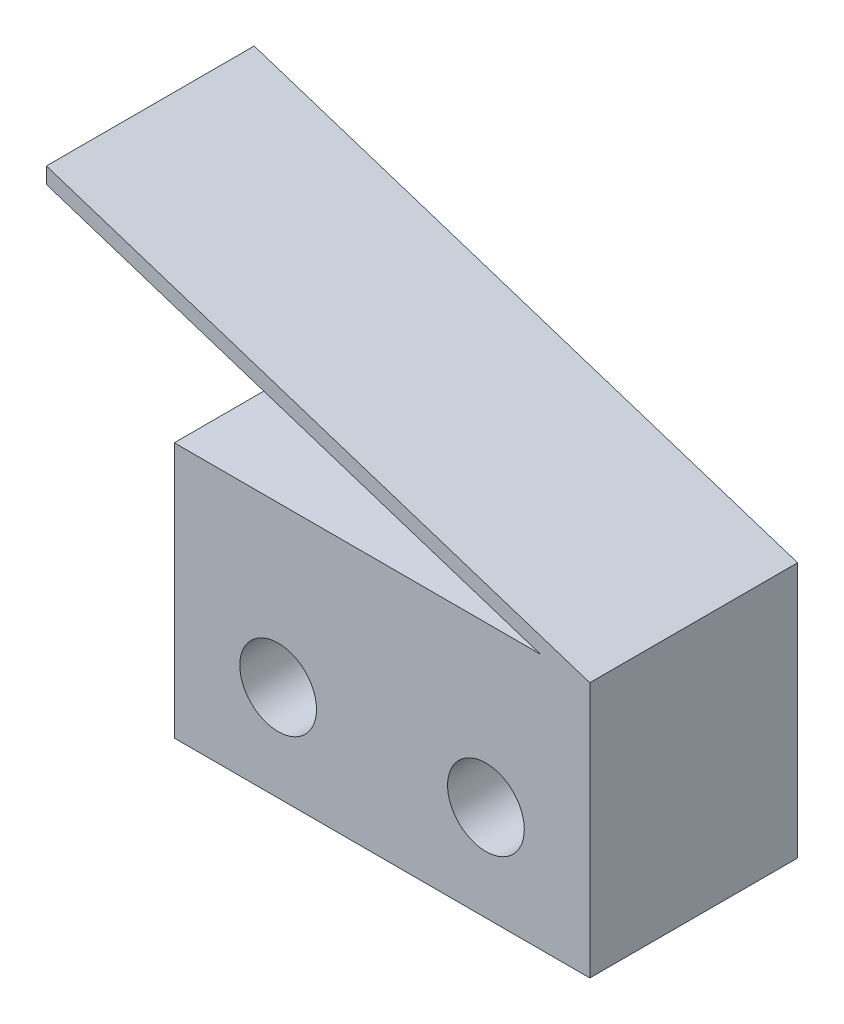
SolidWorks part; units mm, degrees
ref_plane "Ebene vorne" through (0, 0, 0) normal (0, 0, 1) x (1, 0, 0)
ref_plane "Ebene oben" through (0, 0, 0) normal (0, 1, 0) x (1, 0, 0)
ref_plane "Ebene rechts" through (0, 0, 0) normal (1, 0, 0) x (0, 0, -1)
sketch "Skizze1" plane through (0, 0, 0) normal (0, 0, 1) x (1, 0, 0)
  line L0 (0, 0) -> (13, 0)
  line L1 (13, 0) -> (13, 8)
  line L2 (13, 8) -> (-4, 13.5)
  line L3 (-4, 13.5) -> (-4, 13)
  line L4 (-4, 13) -> (11.4545, 8)
  line L5 (11.4545, 8) -> (0, 8)
  line L6 (0, 8) -> (0, 0)
  dimension "D1" = 13
  dimension "D2" = 8
  dimension "D3" = 5
  dimension "D4" = 17
  dimension "D5" = 0.5
extrude "Aufsatz-Linear austragen1" add sketch "Skizze1" along normal blind 6.5
sketch "Skizze2" plane through (0, 0, 6.5) normal (0, 0, 1) x (1, 0, 0)
  line L0 (3.25, 3) -> (9.75, 3) construction
  line L1 (6.5, 3) -> (6.5, 0) construction
  line L2 (0, 0) -> (13, 0) construction
  line L3 (11.4545, 8) -> (0, 8) construction
  circle A0 centre (3.25, 3) radius 1.2
  circle A1 centre (9.75, 3) radius 1.2
  dimension "D1" = 2.4
  dimension "D2" = 6.5
  dimension "D3" = 5
extrude "Schnitt-Linear austragen1" cut sketch "Skizze2" against normal through all
